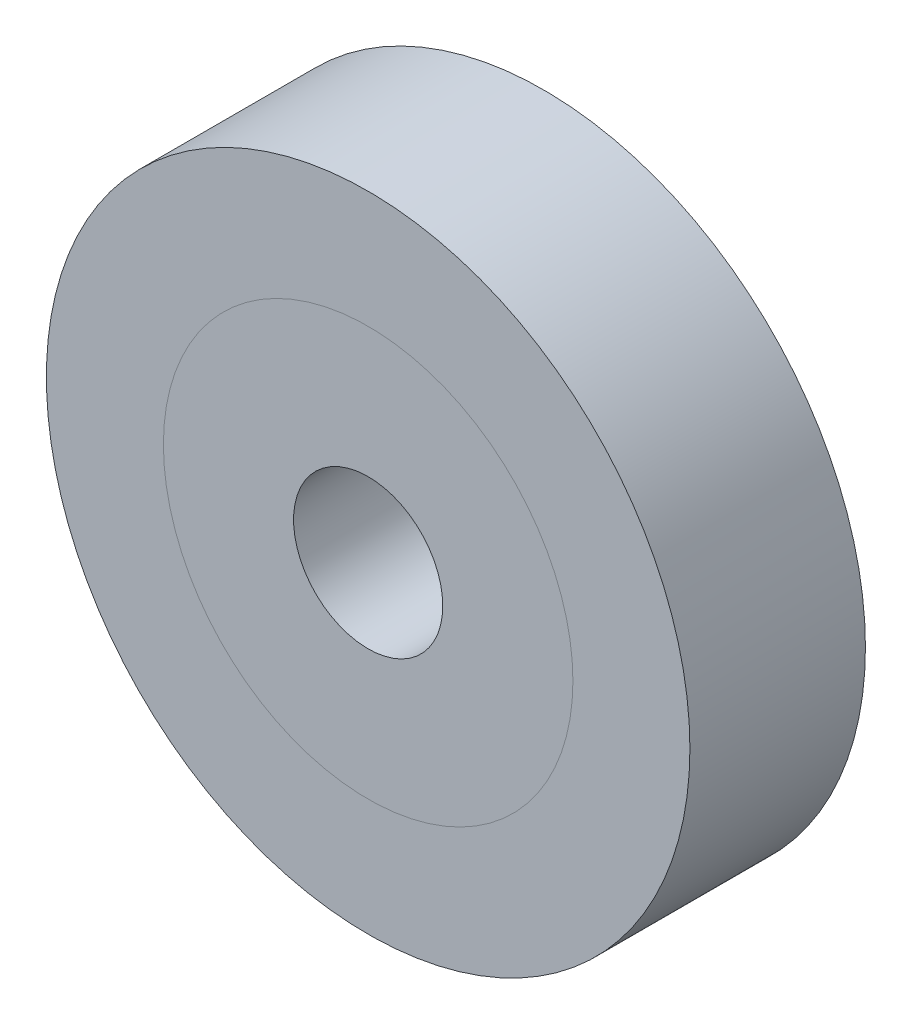
SolidWorks part; units mm, degrees
material "ABS"
ref_plane "前视基准面" through (0, 0, 0) normal (0, 0, 1) x (1, 0, 0)
ref_plane "上视基准面" through (0, 0, 0) normal (0, 1, 0) x (1, 0, 0)
ref_plane "右视基准面" through (0, 0, 0) normal (1, 0, 0) x (0, 0, -1)
sketch "草图1" plane through (0, 0, 0) normal (0, 0, 1) x (1, 0, 0)
  circle A0 centre (0, 0) radius 5.1
  circle A1 centre (0, 0) radius 22
  dimension "D1" = 10.2
  dimension "D2" = 44
extrude "凸台-拉伸1" add sketch "草图1" along normal blind 12
sketch "草图2" plane through (0, 0, 12) normal (0, 0, 1) x (1, 0, 0)
  circle A0 centre (0, 0) radius 14
  dimension "D1" = 28
split "分割1" trim tools "草图2" bodies to split 101 resulting bodies 102 103
